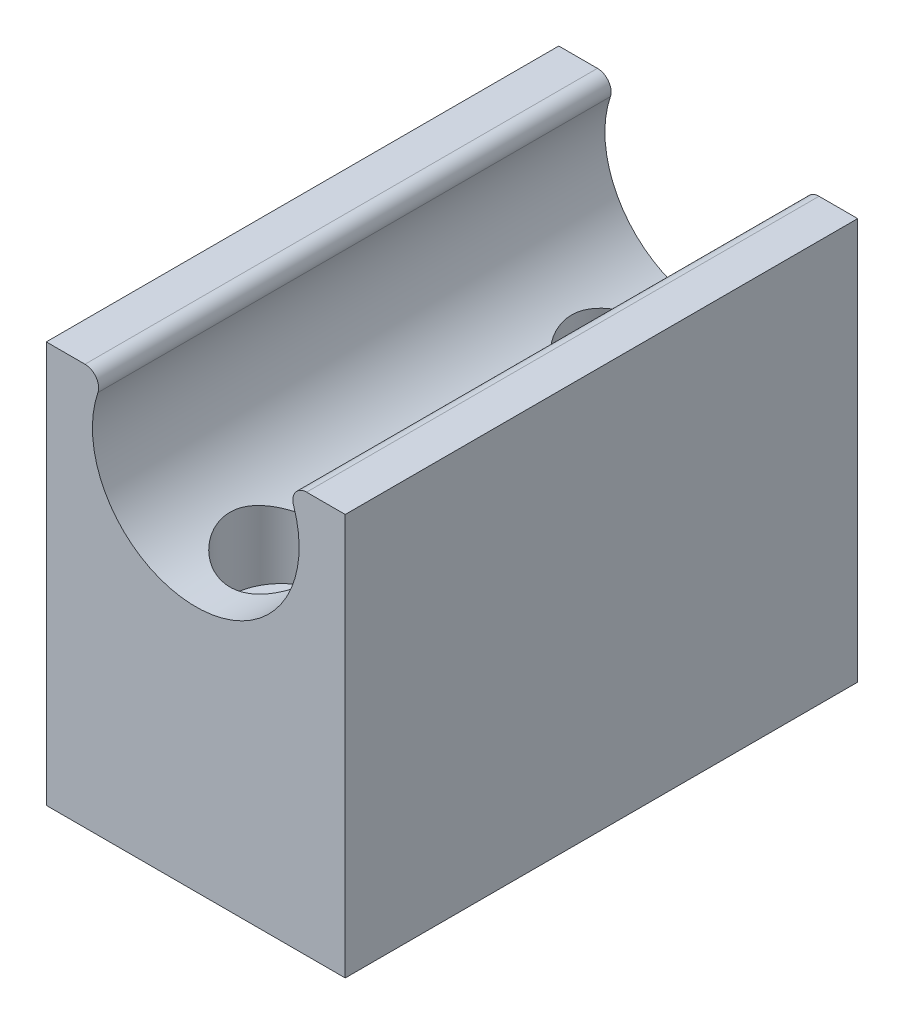
SolidWorks part; units mm, degrees
ref_plane "Front Plane" through (0, 0, 0) normal (0, 0, 1) x (1, 0, 0)
ref_plane "Top Plane" through (0, 0, 0) normal (0, 1, 0) x (1, 0, 0)
ref_plane "Right Plane" through (0, 0, 0) normal (1, 0, 0) x (0, 0, -1)
sketch "Sketch1" plane through (0, 0, 0) normal (0, 0, 1) x (1, 0, 0)
  line L0 (-5.25, 11.75) -> (-8.75, 11.75)
  line L1 (8.75, -11.75) -> (-8.75, -11.75)
  line L2 (8.75, -11.75) -> (8.75, 11.75)
  line L3 (8.75, 11.75) -> (5.25, 11.75)
  line L4 (-8.75, -11.75) -> (-8.75, 11.75)
  line L5 (8.75, -11.75) -> (-8.75, 11.75) construction
  line L6 (8.75, 11.75) -> (-8.75, -11.75) construction
  arc A0 (-5.25, 11.75) -> (5.25, 11.75) centre (0, 8.7433) ccw
  point P0 (0, 0)
  dimension "D1" = 12.1
  dimension "D2" = 3.5
  dimension "D3" = 17.5
  dimension "D4" = 23.5
extrude "Boss-Extrude1" add sketch "Sketch1" along normal blind 30
fillet "Fillet1" radius 0.8 2 edges at (5.25, 11.75, 15) (-5.25, 11.75, 15)
sketch "Sketch3" plane through (0, 11.75, 0) normal (0, 1, 0) x (1, 0, 0)
  line L0 (6.05, 0) -> (-6.05, 0) construction
  line L1 (-6.05, -30) -> (6.05, -30) construction
  circle A0 centre (0, -5) radius 3
  circle A1 centre (0, -25) radius 3
  dimension "D1" = 6
  dimension "D2" = 5
  dimension "D3" = 5
extrude "Cut-Extrude1" cut sketch "Sketch3" against normal blind 12.5
sketch "Sketch4" plane through (0, 11.75, 0) normal (0, 1, 0) x (1, 0, 0)
  circle A0 centre (0, -5) radius 1.55
  circle A1 centre (0, -25) radius 1.55
  dimension "D1" = 3.1
  dimension "D2" = 3.1
extrude "Cut-Extrude2" cut sketch "Sketch4" against normal through all
